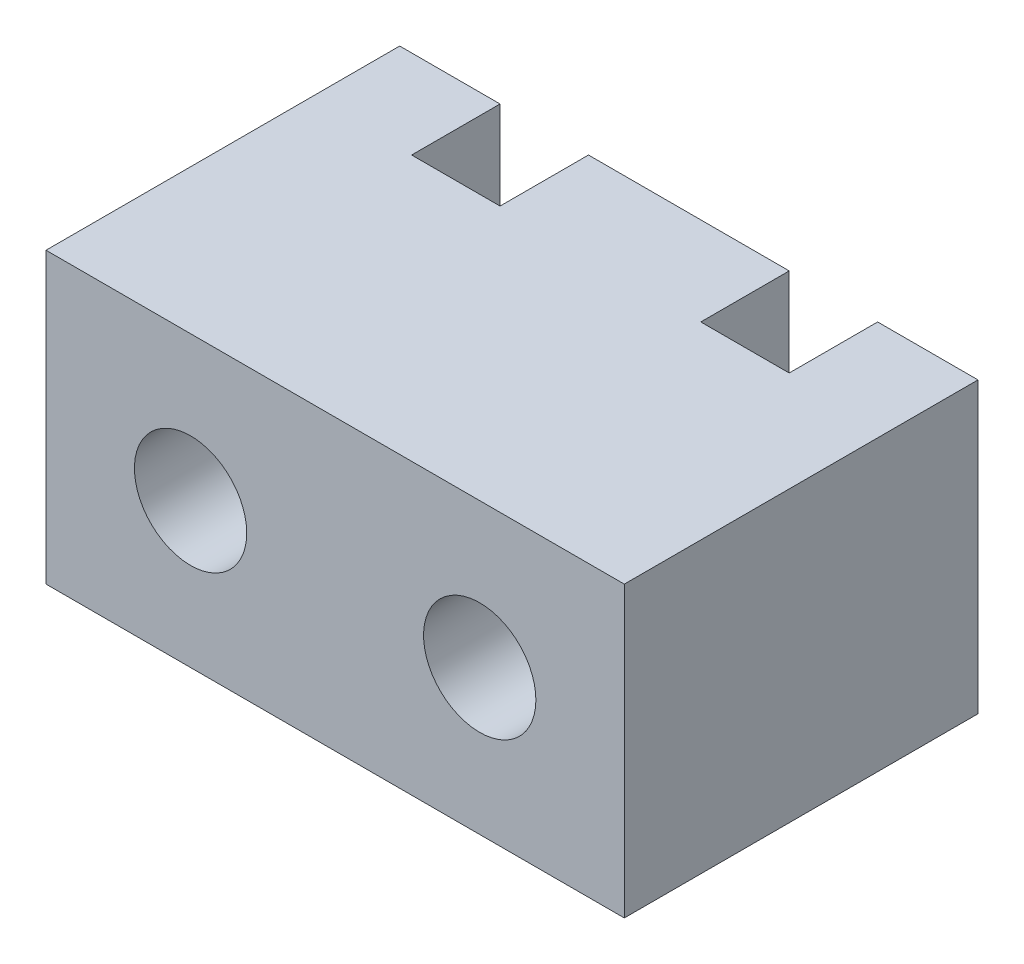
SolidWorks part; units mm, degrees
ref_plane "Front Plane" through (0, 0, 0) normal (0, 0, 1) x (1, 0, 0)
ref_plane "Top Plane" through (0, 0, 0) normal (0, 1, 0) x (1, 0, 0)
ref_plane "Right Plane" through (0, 0, 0) normal (1, 0, 0) x (0, 0, -1)
sketch "Sketch1" plane through (0, 0, 0) normal (0, 0, 1) x (1, 0, 0)
  line L0 (-5, 0) -> (5, 0) construction
  line L1 (-16.35, -8.175) -> (16.35, -8.175)
  line L2 (-16.35, -8.175) -> (-16.35, 8.175)
  line L3 (-16.35, 8.175) -> (16.35, 8.175)
  line L4 (16.35, -8.175) -> (16.35, 8.175)
  line L5 (-16.35, -8.175) -> (16.35, 8.175) construction
  line L6 (-16.35, 8.175) -> (16.35, -8.175) construction
  circle A0 centre (-8.175, 0) radius 3.175
  circle A1 centre (8.175, 0) radius 3.175
  point P0 (0, 0)
  point P12 (11.35, 0)
  point P13 (8.175, -3.175)
  dimension "D1" = 6.35
  dimension "D2" = 10
  dimension "D3" = 5
  dimension "D4" = 5
extrude "Boss-Extrude1" add sketch "Sketch1" along normal mid plane 20
sketch "Sketch2" plane through (0, 0, -10) normal (0, 0, -1) x (-1, 0, 0)
  line L0 (-16.35, 8.175) -> (16.35, 8.175) construction
  line L1 (-10.675, 8.175) -> (-5.675, 8.175)
  line L2 (-10.675, 8.175) -> (-10.675, -8.175)
  line L3 (-10.675, -8.175) -> (-5.675, -8.175)
  line L4 (-5.675, 8.175) -> (-5.675, -8.175)
  line L5 (16.35, -8.175) -> (-16.35, -8.175) construction
  line L7 (5.675, 8.175) -> (10.675, 8.175)
  line L8 (5.675, 8.175) -> (5.675, -8.175)
  line L9 (5.675, -8.175) -> (10.675, -8.175)
  line L10 (10.675, 8.175) -> (10.675, -8.175)
  circle A0 centre (-8.175, 0) radius 3.175 construction
  circle A1 centre (8.175, 0) radius 3.175 construction
  circle A2 centre (-8.175, 0) radius 3.175 construction
  circle A3 centre (8.175, 0) radius 3.175 construction
  point P12 (8.175, 8.175)
  point P19 (0, 0)
  point P20 (-8.175, 8.175)
  point P21 (0, 0)
  dimension "D1" = 5
extrude "Cut-Extrude1" cut sketch "Sketch2" against normal blind 5
